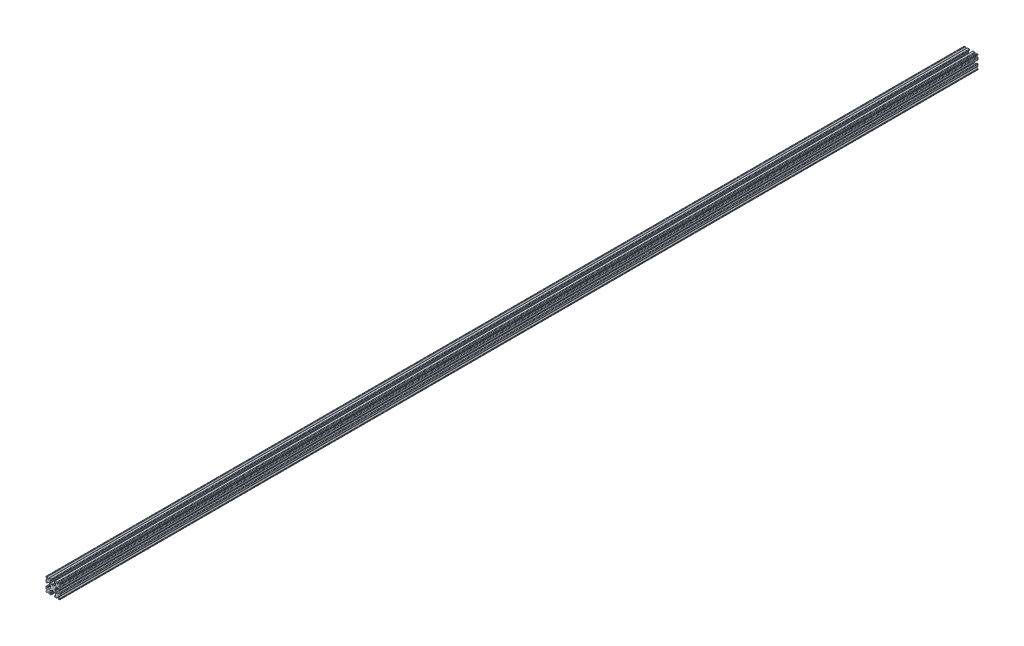
SolidWorks part; units mm, degrees
ref_plane "Front Plane" through (0, 0, 0) normal (0, 0, 1) x (1, 0, 0)
ref_plane "Top Plane" through (0, 0, 0) normal (0, 1, 0) x (1, 0, 0)
ref_plane "Right Plane" through (0, 0, 0) normal (1, 0, 0) x (0, 0, -1)
sketch "Sketch1" plane through (0, 0, 0) normal (0, 0, 1) x (1, 0, 0)
  line L0 (0.8255, -2.5471) -> (0.8255, -2.7749)
  line L1 (0.9818, -2.97) -> (2.5094, -3.3124)
  line L2 (2.9, -3.8003) -> (2.9, -5.9)
  line L3 (2.7, -6.1) -> (2.1, -6.1)
  line L4 (1.6, -6.6) -> (1.6, -7)
  line L5 (2.1, -7.5) -> (3.9, -7.5)
  line L6 (4.4, -7) -> (4.4, -6.6678)
  line L7 (5.2536, -6.3142) -> (6.2929, -7.3536)
  line L8 (6.6464, -7.5) -> (7.25, -7.5)
  line L9 (7.5, -7.25) -> (7.5, -6.6464)
  line L10 (7.3536, -6.2929) -> (6.3142, -5.2536)
  line L11 (6.6678, -4.4) -> (7, -4.4)
  line L12 (7.5, -3.9) -> (7.5, -2.1)
  line L13 (7, -1.6) -> (6.6, -1.6)
  line L14 (6.1, -2.1) -> (6.1, -2.7)
  line L15 (5.9, -2.9) -> (3.8003, -2.9)
  line L16 (3.3124, -2.5094) -> (2.97, -0.9818)
  line L17 (2.7749, -0.8255) -> (2.5471, -0.8255)
  line L18 (2.3471, -0.6255) -> (2.3471, 0.6255)
  line L19 (2.5471, 0.8255) -> (2.7749, 0.8255)
  line L20 (2.97, 0.9818) -> (3.3124, 2.5094)
  line L21 (3.8003, 2.9) -> (5.9, 2.9)
  line L22 (6.1, 2.7) -> (6.1, 2.1)
  line L23 (6.6, 1.6) -> (7, 1.6)
  line L24 (7.5, 2.1) -> (7.5, 3.9)
  line L25 (7, 4.4) -> (6.6678, 4.4)
  line L26 (6.3142, 5.2536) -> (7.3536, 6.2929)
  line L27 (7.5, 6.6464) -> (7.5, 7.25)
  line L28 (7.25, 7.5) -> (6.6464, 7.5)
  line L29 (6.2929, 7.3536) -> (5.2536, 6.3142)
  line L30 (4.4, 6.6678) -> (4.4, 7)
  line L31 (3.9, 7.5) -> (2.1, 7.5)
  line L32 (1.6, 7) -> (1.6, 6.6)
  line L33 (2.1, 6.1) -> (2.7, 6.1)
  line L34 (2.9, 5.9) -> (2.9, 3.8003)
  line L35 (2.5094, 3.3124) -> (0.9818, 2.97)
  line L36 (0.8255, 2.7749) -> (0.8255, 2.5471)
  line L37 (0.6255, 2.3471) -> (-0.6255, 2.3471)
  line L38 (-0.8255, 2.5471) -> (-0.8255, 2.7749)
  line L39 (-0.9818, 2.97) -> (-2.5094, 3.3124)
  line L40 (-2.9, 3.8003) -> (-2.9, 5.9)
  line L41 (-2.7, 6.1) -> (-2.1, 6.1)
  line L42 (-1.6, 6.6) -> (-1.6, 7)
  line L43 (-2.1, 7.5) -> (-3.9, 7.5)
  line L44 (-4.4, 7) -> (-4.4, 6.6678)
  line L45 (-5.2536, 6.3142) -> (-6.2929, 7.3536)
  line L46 (-6.6464, 7.5) -> (-7.25, 7.5)
  line L47 (-7.5, 7.25) -> (-7.5, 6.6464)
  line L48 (-7.3536, 6.2929) -> (-6.3142, 5.2536)
  line L49 (-6.6678, 4.4) -> (-7, 4.4)
  line L50 (-7.5, 3.9) -> (-7.5, 2.1)
  line L51 (-7, 1.6) -> (-6.6, 1.6)
  line L52 (-6.1, 2.1) -> (-6.1, 2.7)
  line L53 (-5.9, 2.9) -> (-3.8003, 2.9)
  line L54 (-3.3124, 2.5094) -> (-2.97, 0.9818)
  line L55 (-2.7749, 0.8255) -> (-2.5471, 0.8255)
  line L56 (-2.3471, 0.6255) -> (-2.3471, -0.6255)
  line L57 (-2.5471, -0.8255) -> (-2.7749, -0.8255)
  line L58 (-2.97, -0.9818) -> (-3.3124, -2.5094)
  line L59 (-3.8003, -2.9) -> (-5.9, -2.9)
  line L60 (-6.1, -2.7) -> (-6.1, -2.1)
  line L61 (-6.6, -1.6) -> (-7, -1.6)
  line L62 (-7.5, -2.1) -> (-7.5, -3.9)
  line L63 (-7, -4.4) -> (-6.6678, -4.4)
  line L64 (-6.3142, -5.2536) -> (-7.3536, -6.2929)
  line L65 (-7.5, -6.6464) -> (-7.5, -7.25)
  line L66 (-7.25, -7.5) -> (-6.6464, -7.5)
  line L67 (-6.2929, -7.3536) -> (-5.2536, -6.3142)
  line L68 (-4.4, -6.6678) -> (-4.4, -7)
  line L69 (-3.9, -7.5) -> (-2.1, -7.5)
  line L70 (-1.6, -7) -> (-1.6, -6.6)
  line L71 (-2.1, -6.1) -> (-2.7, -6.1)
  line L72 (-2.9, -5.9) -> (-2.9, -3.8003)
  line L73 (-2.5094, -3.3124) -> (-0.9818, -2.97)
  line L74 (-0.8255, -2.7749) -> (-0.8255, -2.5471)
  line L75 (-0.6255, -2.3471) -> (0.6255, -2.3471)
  arc A0 (0.8255, -2.7749) -> (0.9818, -2.97) centre (1.0255, -2.7749) ccw
  arc A1 (2.9, -3.8003) -> (2.5094, -3.3124) centre (2.4, -3.8003) ccw
  arc A2 (2.7, -6.1) -> (2.9, -5.9) centre (2.7, -5.9) ccw
  arc A3 (2.1, -6.1) -> (1.6, -6.6) centre (2.1, -6.6) ccw
  arc A4 (1.6, -7) -> (2.1, -7.5) centre (2.1, -7) ccw
  arc A5 (3.9, -7.5) -> (4.4, -7) centre (3.9, -7) ccw
  arc A6 (5.2536, -6.3142) -> (4.4, -6.6678) centre (4.9, -6.6678) ccw
  arc A7 (6.2929, -7.3536) -> (6.6464, -7.5) centre (6.6464, -7) ccw
  arc A8 (7.25, -7.5) -> (7.5, -7.25) centre (7.25, -7.25) ccw
  arc A9 (7.5, -6.6464) -> (7.3536, -6.2929) centre (7, -6.6464) ccw
  arc A10 (6.6678, -4.4) -> (6.3142, -5.2536) centre (6.6678, -4.9) ccw
  arc A11 (7, -4.4) -> (7.5, -3.9) centre (7, -3.9) ccw
  arc A12 (7.5, -2.1) -> (7, -1.6) centre (7, -2.1) ccw
  arc A13 (6.6, -1.6) -> (6.1, -2.1) centre (6.6, -2.1) ccw
  arc A14 (5.9, -2.9) -> (6.1, -2.7) centre (5.9, -2.7) ccw
  arc A15 (3.3124, -2.5094) -> (3.8003, -2.9) centre (3.8003, -2.4) ccw
  arc A16 (2.97, -0.9818) -> (2.7749, -0.8255) centre (2.7749, -1.0255) ccw
  arc A17 (2.3471, -0.6255) -> (2.5471, -0.8255) centre (2.5471, -0.6255) ccw
  arc A18 (2.5471, 0.8255) -> (2.3471, 0.6255) centre (2.5471, 0.6255) ccw
  arc A19 (2.7749, 0.8255) -> (2.97, 0.9818) centre (2.7749, 1.0255) ccw
  arc A20 (3.8003, 2.9) -> (3.3124, 2.5094) centre (3.8003, 2.4) ccw
  arc A21 (6.1, 2.7) -> (5.9, 2.9) centre (5.9, 2.7) ccw
  arc A22 (6.1, 2.1) -> (6.6, 1.6) centre (6.6, 2.1) ccw
  arc A23 (7, 1.6) -> (7.5, 2.1) centre (7, 2.1) ccw
  arc A24 (7.5, 3.9) -> (7, 4.4) centre (7, 3.9) ccw
  arc A25 (6.3142, 5.2536) -> (6.6678, 4.4) centre (6.6678, 4.9) ccw
  arc A26 (7.3536, 6.2929) -> (7.5, 6.6464) centre (7, 6.6464) ccw
  arc A27 (7.5, 7.25) -> (7.25, 7.5) centre (7.25, 7.25) ccw
  arc A28 (6.6464, 7.5) -> (6.2929, 7.3536) centre (6.6464, 7) ccw
  arc A29 (4.4, 6.6678) -> (5.2536, 6.3142) centre (4.9, 6.6678) ccw
  arc A30 (4.4, 7) -> (3.9, 7.5) centre (3.9, 7) ccw
  arc A31 (2.1, 7.5) -> (1.6, 7) centre (2.1, 7) ccw
  arc A32 (1.6, 6.6) -> (2.1, 6.1) centre (2.1, 6.6) ccw
  arc A33 (2.9, 5.9) -> (2.7, 6.1) centre (2.7, 5.9) ccw
  arc A34 (2.5094, 3.3124) -> (2.9, 3.8003) centre (2.4, 3.8003) ccw
  arc A35 (0.9818, 2.97) -> (0.8255, 2.7749) centre (1.0255, 2.7749) ccw
  arc A36 (0.6255, 2.3471) -> (0.8255, 2.5471) centre (0.6255, 2.5471) ccw
  arc A37 (-0.8255, 2.5471) -> (-0.6255, 2.3471) centre (-0.6255, 2.5471) ccw
  arc A38 (-0.8255, 2.7749) -> (-0.9818, 2.97) centre (-1.0255, 2.7749) ccw
  arc A39 (-2.9, 3.8003) -> (-2.5094, 3.3124) centre (-2.4, 3.8003) ccw
  arc A40 (-2.7, 6.1) -> (-2.9, 5.9) centre (-2.7, 5.9) ccw
  arc A41 (-2.1, 6.1) -> (-1.6, 6.6) centre (-2.1, 6.6) ccw
  arc A42 (-1.6, 7) -> (-2.1, 7.5) centre (-2.1, 7) ccw
  arc A43 (-3.9, 7.5) -> (-4.4, 7) centre (-3.9, 7) ccw
  arc A44 (-5.2536, 6.3142) -> (-4.4, 6.6678) centre (-4.9, 6.6678) ccw
  arc A45 (-6.2929, 7.3536) -> (-6.6464, 7.5) centre (-6.6464, 7) ccw
  arc A46 (-7.25, 7.5) -> (-7.5, 7.25) centre (-7.25, 7.25) ccw
  arc A47 (-7.5, 6.6464) -> (-7.3536, 6.2929) centre (-7, 6.6464) ccw
  arc A48 (-6.6678, 4.4) -> (-6.3142, 5.2536) centre (-6.6678, 4.9) ccw
  arc A49 (-7, 4.4) -> (-7.5, 3.9) centre (-7, 3.9) ccw
  arc A50 (-7.5, 2.1) -> (-7, 1.6) centre (-7, 2.1) ccw
  arc A51 (-6.6, 1.6) -> (-6.1, 2.1) centre (-6.6, 2.1) ccw
  arc A52 (-5.9, 2.9) -> (-6.1, 2.7) centre (-5.9, 2.7) ccw
  arc A53 (-3.3124, 2.5094) -> (-3.8003, 2.9) centre (-3.8003, 2.4) ccw
  arc A54 (-2.97, 0.9818) -> (-2.7749, 0.8255) centre (-2.7749, 1.0255) ccw
  arc A55 (-2.3471, 0.6255) -> (-2.5471, 0.8255) centre (-2.5471, 0.6255) ccw
  arc A56 (-2.5471, -0.8255) -> (-2.3471, -0.6255) centre (-2.5471, -0.6255) ccw
  arc A57 (-2.7749, -0.8255) -> (-2.97, -0.9818) centre (-2.7749, -1.0255) ccw
  arc A58 (-3.8003, -2.9) -> (-3.3124, -2.5094) centre (-3.8003, -2.4) ccw
  arc A59 (-6.1, -2.7) -> (-5.9, -2.9) centre (-5.9, -2.7) ccw
  arc A60 (-6.1, -2.1) -> (-6.6, -1.6) centre (-6.6, -2.1) ccw
  arc A61 (-7, -1.6) -> (-7.5, -2.1) centre (-7, -2.1) ccw
  arc A62 (-7.5, -3.9) -> (-7, -4.4) centre (-7, -3.9) ccw
  arc A63 (-6.3142, -5.2536) -> (-6.6678, -4.4) centre (-6.6678, -4.9) ccw
  arc A64 (-7.3536, -6.2929) -> (-7.5, -6.6464) centre (-7, -6.6464) ccw
  arc A65 (-7.5, -7.25) -> (-7.25, -7.5) centre (-7.25, -7.25) ccw
  arc A66 (-6.6464, -7.5) -> (-6.2929, -7.3536) centre (-6.6464, -7) ccw
  arc A67 (-4.4, -6.6678) -> (-5.2536, -6.3142) centre (-4.9, -6.6678) ccw
  arc A68 (-4.4, -7) -> (-3.9, -7.5) centre (-3.9, -7) ccw
  arc A69 (-2.1, -7.5) -> (-1.6, -7) centre (-2.1, -7) ccw
  arc A70 (-1.6, -6.6) -> (-2.1, -6.1) centre (-2.1, -6.6) ccw
  arc A71 (-2.9, -5.9) -> (-2.7, -6.1) centre (-2.7, -5.9) ccw
  arc A72 (-2.5094, -3.3124) -> (-2.9, -3.8003) centre (-2.4, -3.8003) ccw
  arc A73 (-0.9818, -2.97) -> (-0.8255, -2.7749) centre (-1.0255, -2.7749) ccw
  arc A74 (-0.6255, -2.3471) -> (-0.8255, -2.5471) centre (-0.6255, -2.5471) ccw
  arc A75 (0.8255, -2.5471) -> (0.6255, -2.3471) centre (0.6255, -2.5471) ccw
extrude "Boss-Extrude1" add sketch "Sketch1" along normal blind 1000
